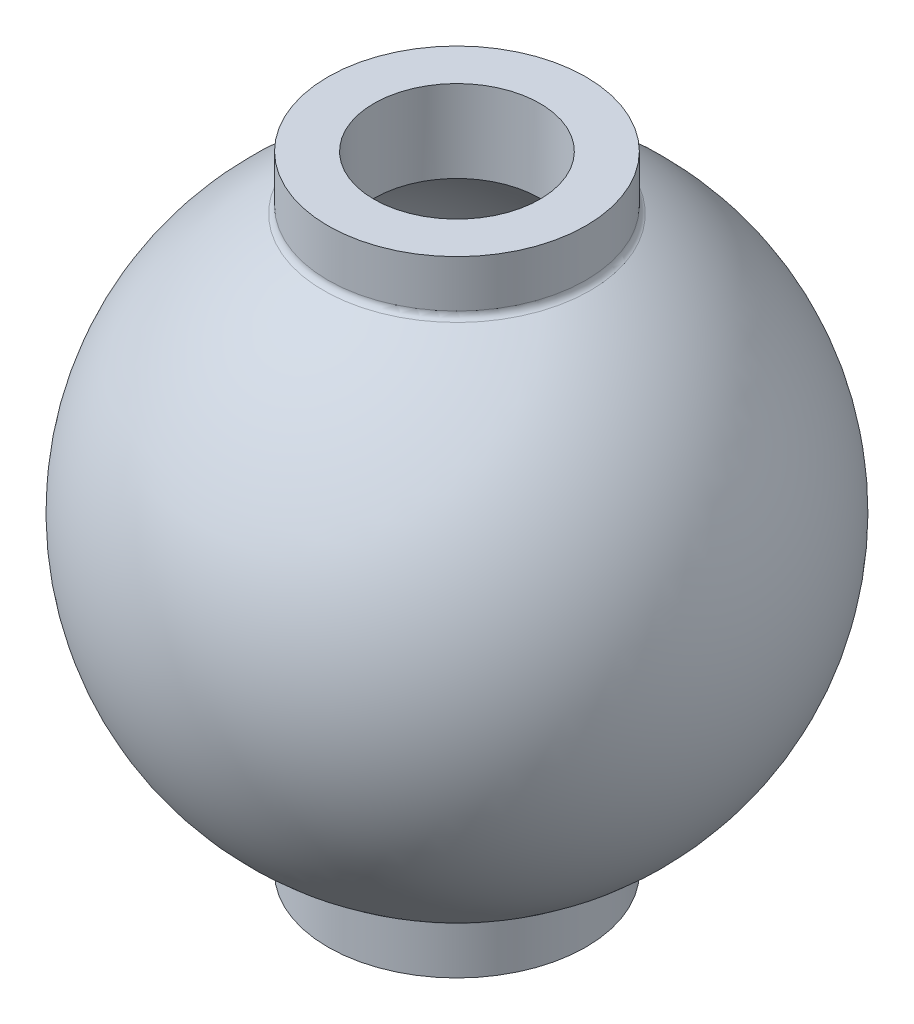
SolidWorks part; units mm, degrees
material "Acrylic (Medium-high impact)"
ref_plane "Front Plane" through (0, 0, 0) normal (0, 0, 1) x (1, 0, 0)
ref_plane "Top Plane" through (0, 0, 0) normal (0, 1, 0) x (1, 0, 0)
ref_plane "Right Plane" through (0, 0, 0) normal (1, 0, 0) x (0, 0, -1)
sketch "Sketch1" plane through (0, 0, 0) normal (0, 0, 1) x (1, 0, 0)
  line L0 (0, 1478.8632) -> (0, -1200.3639) construction
  line L1 (0, 1203.6392) -> (320, 1203.6392)
  line L2 (320, 1203.6392) -> (320, 1073.3126)
  line L3 (320, 1203.6392) -> (497.1, 1203.6392)
  line L4 (497.1, 1203.6392) -> (497.1, 1003.6392)
  line L5 (0, -1203.6392) -> (497.1, -1203.6392)
  line L6 (497.1, -1203.6392) -> (497.1, -1003.6392)
  line L7 (320, -1203.6392) -> (320, -1073.3126)
  arc A0 (0, 942.9) -> (0, -942.9) centre (0, 0) cw
  arc A1 (0, -1120) -> (0, 1120) centre (0, 0) ccw
  dimension "D1" = 942.9
  dimension "D2" = 1120
  dimension "D3" = 320
  dimension "D4" = 177.1
  dimension "D5" = 200
revolve "Revolve1" add sketch "Sketch1" angle 360 about L0
sketch "Sketch2" plane through (0, 1203.6392, 0) normal (0, 1, 0) x (1, 0, 0)
  circle A0 centre (0, 0) radius 320
  dimension "D1" = 640
extrude "Cut-Extrude1" cut sketch "Sketch2" against normal blind 1120
fillet "Fillet1" radius 30 2 edges at (0, 1003.6392, 497.1) (0, -1003.6392, 497.1)
sketch "Sketch3" plane through (0, 0, 0) normal (0, 1, 0) x (1, 0, 0)
  point P0 (0, 0)
sketch "Sketch4" plane through (0, -1203.6392, 0) normal (0, -1, 0) x (1, 0, 0)
  circle A0 centre (0, 0) radius 300
  circle A1 centre (0, 0) radius 320 construction
  dimension "D1" = 20
extrude "Boss-Extrude1" add sketch "Sketch4" against normal blind 160
equation "\"hatchHoleDiameter\"=600mm"
equation "\"hullThickness\"=177.1mm"
equation "\"gasketHullInterconnectWidth\"=100mm"
equation "\"collarThickness\"=20mm"
equation "\"hatchTunnelLength\"=200mm"
equation "\"oRingDiameter\"=2mm"
equation "\"boltPatternRadiusInterconnect\"=500mm"
equation "\"interconnectBoltDiameter\"=30mm"
equation "\"hatchShaftDiameter\"=20mm"
equation "\"hatchMinima\"=39.9mm"
equation "\"hullDiameter\"=2240mm"
equation "\"hatchMaxima\"=180mm"
equation "\"bushingFlatHatch\"=15mm"
equation "\"hingePivotDiameter\"=20mm"
equation "\"handleWidth\"=250mm"
equation "\"handleHeight\"=160mm"
equation "\"handleThickness\"=25mm"
equation "\"D2@Sketch1\"=\"hullDiameter\"/2"
equation "\"D1@Sketch1\"=\"hullDiameter\"/2 - \"hullThickness\""
equation "\"D3@Sketch1\"=\"hatchHoleDiameter\"/2 + \"collarThickness\""
equation "\"D4@Sketch1\"=\"hullThickness\""
equation "\"D1@Sketch2\"=\"hatchHoleDiameter\" + 2*\"collarThickness\""
equation "\"D1@Cut-Extrude1\"=\"hullDiameter\"/2"
equation "\"D1@Sketch4\"=\"collarThickness\""
equation "\"hatchHcollarThicknessoleDiameter\"=20mm"
equation "\"hatchTopToDogArmCenter\"=33mm"
equation "\"dogArmSize\"=30mm"
equation "\"hatchPivotHeight\"=40mm"
equation "\"hatchPivotDistance\"=70mm"
equation "\"HatchORingDiameter\"=2.1mm"
equation "\"FrameLength\"=2600mm"
equation "\"FrameMidLength\"=1800mm"
equation "\"TubeOD\"=100mm"
equation "\"FrameBackFlat\"=500mm"
equation "\"TubeWall\"=15.0001mm"
equation "\"TopMemberAngle\"=140deg"
equation "\"hatchThickness\"=39.9mm"
equation "\"hatchEdgeToTop\"=76.7095mm"
equation "\"mountAngle\"=70.9702deg"
equation "\"ThrusterDim\"=160.5mm"
equation "\"FrameHight\"=2500mm"
equation "\"HatchShaftSeatThickness\"=20mm"
